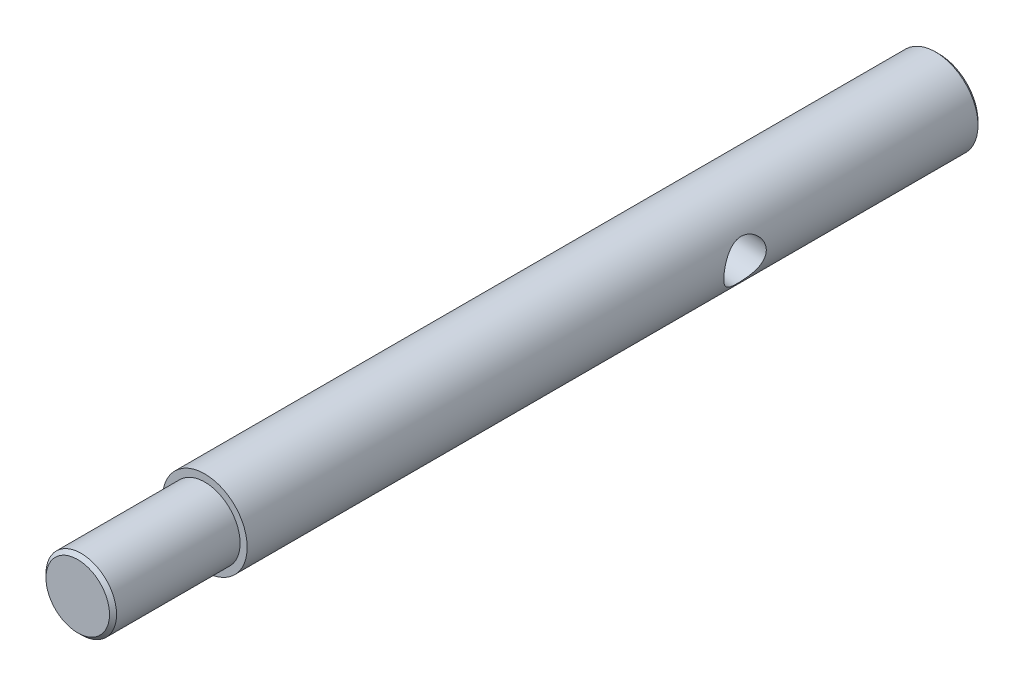
SolidWorks part; units mm, degrees
material "Cast Stainless Steel"
ref_plane "Front Plane" through (0, 0, 0) normal (0, 0, 1) x (1, 0, 0)
ref_plane "Top Plane" through (0, 0, 0) normal (0, 1, 0) x (1, 0, 0)
ref_plane "Right Plane" through (0, 0, 0) normal (1, 0, 0) x (0, 0, -1)
sketch "Sketch1" plane through (0, 0, 0) normal (0, 0, 1) x (1, 0, 0)
  circle A0 centre (0, 0) radius 3
  dimension "D1" = 6
extrude "Boss-Extrude1" add sketch "Sketch1" along normal blind 52
sketch "Sketch2" plane through (0, 0, 52) normal (0, 0, 1) x (1, 0, 0)
  circle A0 centre (0, 0) radius 2.5
  dimension "D1" = 5
extrude "Boss-Extrude2" add sketch "Sketch2" along normal blind 9
chamfer "Chamfer1" distance 0.25 angle 45 1 edges at (2.5, 0, 61)
chamfer "Chamfer2" distance 0.25 angle 45 1 edges at (3, 0, 0)
hole_wizard "Ø3.0mm Dowel Hole1" positions "3DSketch1" profile "Sketch3" hole size "Ø3.0" standard "ISO" end condition through all
sketch3d "3DSketch1"
  point P0 (2.9906, -0.2373, 16.7332)
  dimension "D1" = 17
sketch "Sketch3" plane through (2.9906, -0.2373, 16.7332) normal (0, 0, 1) x (0.0791, 0.9969, 0)
  line L0 (0, 0) -> (0, 6.2279)
  line L1 (0, 6.2279) -> (1.5, 6.2279)
  line L2 (1.5, 6.2279) -> (1.5, 0)
  line L5 (1.5, 0) -> (0, 0)
  line L11 (0, -6.35) -> (0, 107.95) construction
  dimension "Thru Hole Dia." = 3
  dimension "Thru Hole Depth" = 6.2279
